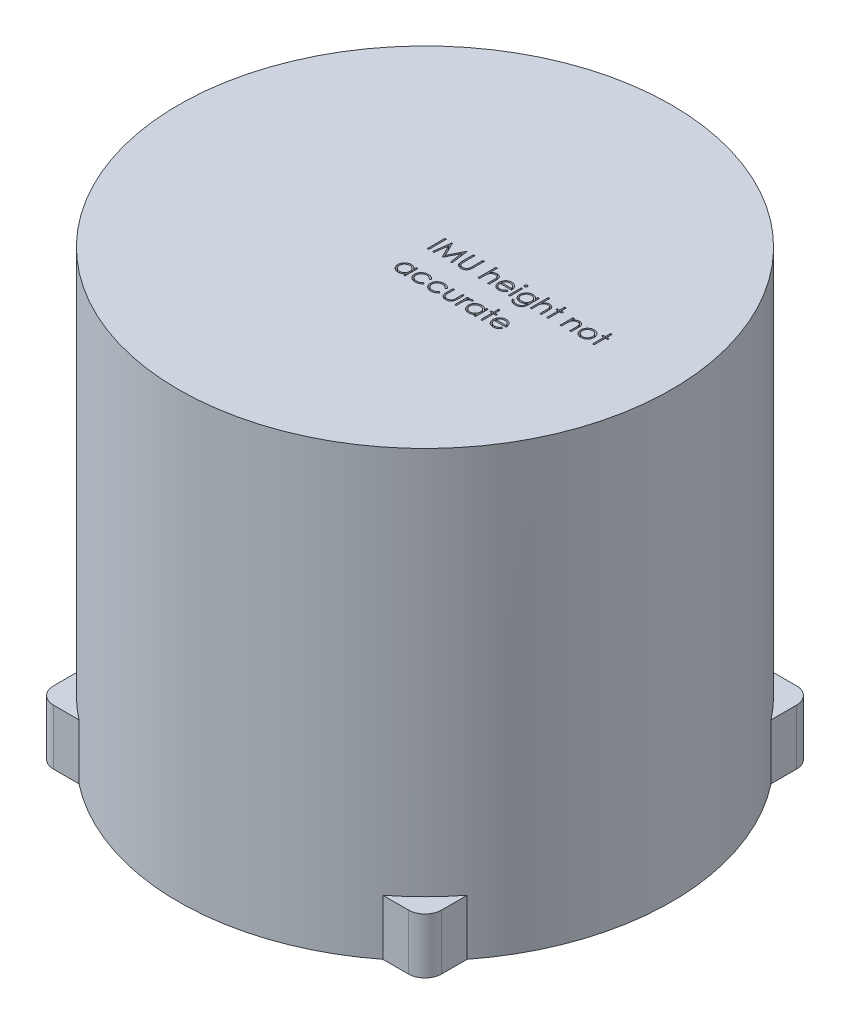
SolidWorks part; units mm, degrees
ref_plane "Front Plane" through (0, 0, 0) normal (0, 0, 1) x (1, 0, 0)
ref_plane "Top Plane" through (0, 0, 0) normal (0, 1, 0) x (1, 0, 0)
ref_plane "Right Plane" through (0, 0, 0) normal (1, 0, 0) x (0, 0, -1)
sketch "Sketch1" plane through (0, 0, 0) normal (0, 1, 0) x (1, 0, 0)
  line L0 (27.4008, 35) -> (32, 35)
  line L1 (-32, -35) -> (-27.4008, -35)
  line L2 (-35, -32) -> (-35, -27.4008)
  line L3 (-32, 35) -> (-27.4008, 35)
  line L4 (35, -32) -> (35, -27.4008)
  line L5 (-35, -35) -> (35, 35) construction
  line L6 (-35, 35) -> (35, -35) construction
  line L7 (-35, 27.4008) -> (-35, 32)
  line L8 (35, 27.4008) -> (35, 32)
  line L9 (27.4008, -35) -> (32, -35)
  arc A0 (-35, 27.4008) -> (-35, -27.4008) centre (0, 0) ccw
  arc A1 (-32, -35) -> (-35, -32) centre (-32, -32) cw
  arc A2 (32, -35) -> (35, -32) centre (32, -32) ccw
  arc A3 (32, 35) -> (35, 32) centre (32, 32) cw
  arc A4 (-35, 32) -> (-32, 35) centre (-32, 32) cw
  arc A5 (-27.4008, -35) -> (27.4008, -35) centre (0, 0) ccw
  arc A6 (35, -27.4008) -> (35, 27.4008) centre (0, 0) ccw
  arc A7 (27.4008, 35) -> (-27.4008, 35) centre (0, 0) ccw
  dimension "D1" = 88.9
  dimension "D3" = 3
  dimension "D2" = 70
extrude "Boss-Extrude1" add sketch "Sketch1" along normal blind 10
sketch "Sketch2" plane through (0, 10, 0) normal (0, 1, 0) x (1, 0, 0)
  circle A0 centre (0, 0) radius 44.45
extrude "Boss-Extrude2" add sketch "Sketch2" along normal blind 70
sketch "Sketch3" plane through (0, 80, 0) normal (0, 1, 0) x (1, 0, 0)
  text T0 "IMU height not\r\naccurate"
extrude "Cut-Extrude1" cut sketch "Sketch3" against normal blind 10
